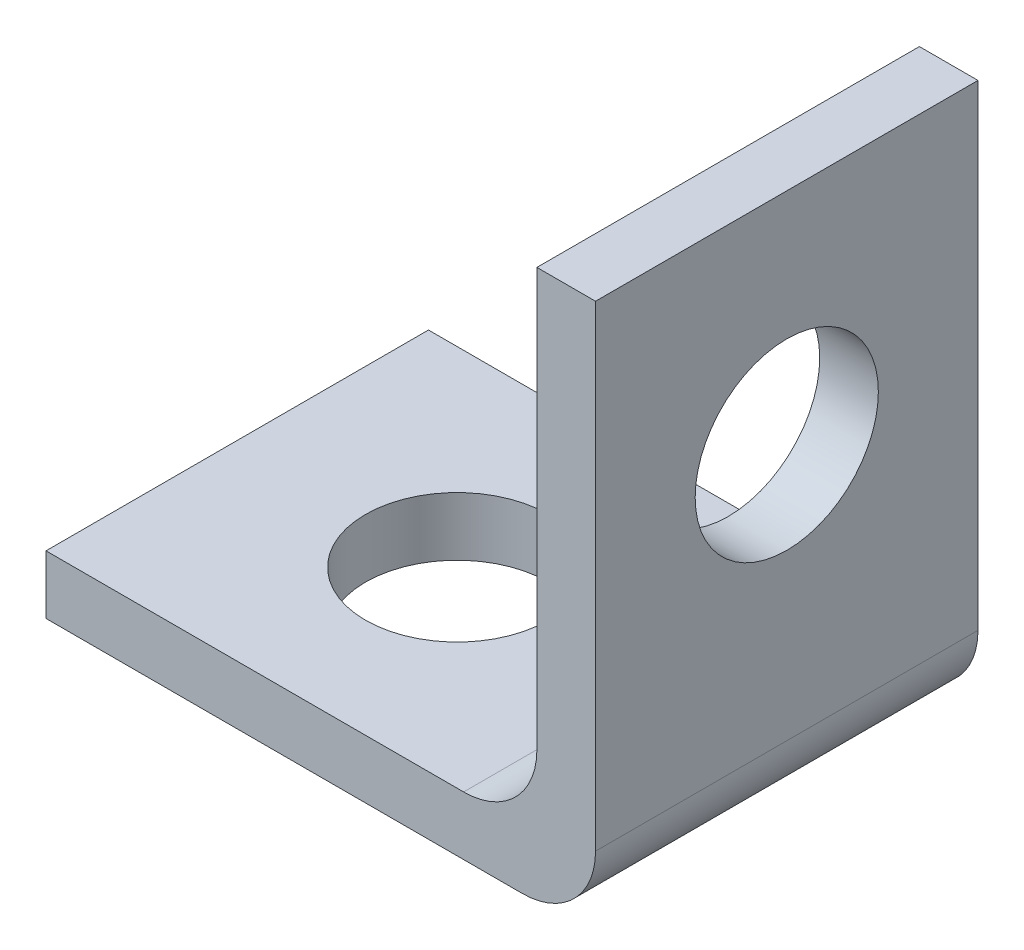
SolidWorks part; units mm, degrees
ref_plane "Front Plane" through (0, 0, 0) normal (0, 0, 1) x (1, 0, 0)
ref_plane "Top Plane" through (0, 0, 0) normal (0, 1, 0) x (1, 0, 0)
ref_plane "Right Plane" through (0, 0, 0) normal (1, 0, 0) x (0, 0, -1)
sketch "Sketch1" plane through (0, 0, 0) normal (0, 0, 1) x (1, 0, 0)
  line L0 (7.493, 1.016) -> (7.493, 18.034)
  line L1 (9.525, -1.016) -> (-9.525, -1.016)
  line L3 (7.493, 1.016) -> (-9.525, 1.016)
  line L4 (-9.525, -1.016) -> (-9.525, 1.016)
  line L5 (9.525, -1.016) -> (-9.525, 1.016) construction
  line L6 (9.525, 1.016) -> (-9.525, -1.016) construction
  line L9 (7.493, 18.034) -> (9.525, 18.034)
  line L10 (9.525, -1.016) -> (9.525, 18.034)
  point P0 (0, 0)
  point P6 (0, 0)
  point P10 (0, 0)
  point P11 (0, 0)
  point P12 (7.355, 0.4861)
  dimension "D1" = 19.05
  dimension "D2" = 2.032
  dimension "D3" = 2.032
extrude "Boss-Extrude1" add sketch "Sketch1" along normal blind 6.6294 and the other way blind 6.6294
sketch "Sketch2" plane through (0, 1.016, 0) normal (0, 1, 0) x (1, 0, 0)
  line L0 (-9.525, 6.6294) -> (-9.525, -6.6294) construction
  circle A0 centre (-1.905, 0) radius 3.175 construction
  point P2 (0, 0)
  dimension "D2" = 6.35
  dimension "D1" = 7.62
sketch "Sketch3" plane through (7.493, 0, 0) normal (-1, 0, 0) x (0, 0, 1)
  line L0 (-6.6294, 18.034) -> (6.6294, 18.034) construction
  circle A0 centre (0, 10.414) radius 3.175 construction
  dimension "D2" = 6.35
  dimension "D1" = 7.62
hole_wizard "1/4 (0.2500) Dowel Hole1" positions "Sketch4" profile "Sketch5" hole size "1/4" standard "ANSI Inch" end condition through all
sketch "Sketch4" plane through (0, 1.016, 0) normal (0, 1, 0) x (1, 0, 0)
  point P0 (-1.905, 0)
sketch "Sketch5" plane through (-1.905, 1.016, 0) normal (1, 0, 0) x (0, 0, 1)
  line L0 (0, 0) -> (0, 2.032)
  line L1 (0, 2.032) -> (3.175, 2.032)
  line L2 (3.175, 2.032) -> (3.175, 0)
  line L5 (3.175, 0) -> (0, 0)
  line L11 (0, -6.35) -> (0, 107.95) construction
  dimension "Thru Hole Dia." = 6.35
  dimension "Thru Hole Depth" = 2.032
hole_wizard "1/4 (0.2500) Dowel Hole2" positions "Sketch6" profile "Sketch7" hole size "1/4" standard "ANSI Inch" end condition through all
sketch "Sketch6" plane through (7.493, 0, 0) normal (-1, 0, 0) x (0, 0, 1)
  point P0 (0, 10.414)
sketch "Sketch7" plane through (7.493, 10.414, 0) normal (0, 1, 0) x (0, 0, 1)
  line L0 (0, 0) -> (0, 2.032)
  line L1 (0, 2.032) -> (3.175, 2.032)
  line L2 (3.175, 2.032) -> (3.175, 0)
  line L5 (3.175, 0) -> (0, 0)
  line L11 (0, -6.35) -> (0, 107.95) construction
  dimension "Thru Hole Dia." = 6.35
  dimension "Thru Hole Depth" = 2.032
fillet "Fillet1" radius 2.54 2 edges at (9.525, -1.016, 0) (7.493, 1.016, 0)
